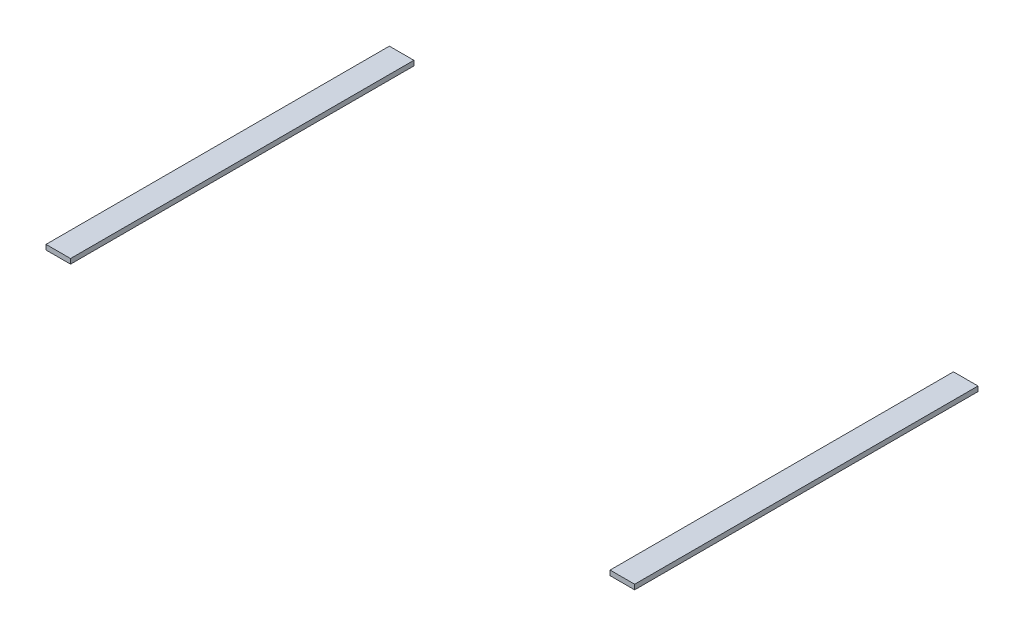
SolidWorks part; units mm, degrees
ref_plane "Front Plane" through (0, 0, 0) normal (0, 0, 1) x (1, 0, 0)
ref_plane "Top Plane" through (0, 0, 0) normal (0, 1, 0) x (1, 0, 0)
ref_plane "Right Plane" through (0, 0, 0) normal (1, 0, 0) x (0, 0, -1)
sketch "Sketch1" plane through (0, 0, 0) normal (0, 1, 0) x (1, 0, 0)
  line L1 (120, -70) -> (-120, -70)
  line L2 (120, -70) -> (120, 70)
  line L3 (120, 70) -> (-120, 70)
  line L4 (-120, -70) -> (-120, 70)
  line L5 (120, -70) -> (-120, 70) construction
  line L6 (120, 70) -> (-120, -70) construction
  point P0 (0, 0)
  dimension "D1" = 240
  dimension "D2" = 140
extrude "Boss-Extrude1" add sketch "Sketch1" along normal blind 2
sketch "Sketch2" plane through (0, 0, 0) normal (0, 1, 0) x (1, 0, 0)
  line L0 (120, 70) -> (-120, 70) construction
  line L1 (-110, 70) -> (110, 70)
  line L2 (-110, 70) -> (-110, -70)
  line L3 (-110, -70) -> (110, -70)
  line L4 (110, 70) -> (110, -70)
  line L5 (-120, 70) -> (-120, -70) construction
  dimension "D1" = 10
  dimension "D2" = 10
  dimension "D3" = 140
extrude "Cut-Extrude1" cut sketch "Sketch2" along normal blind 2
